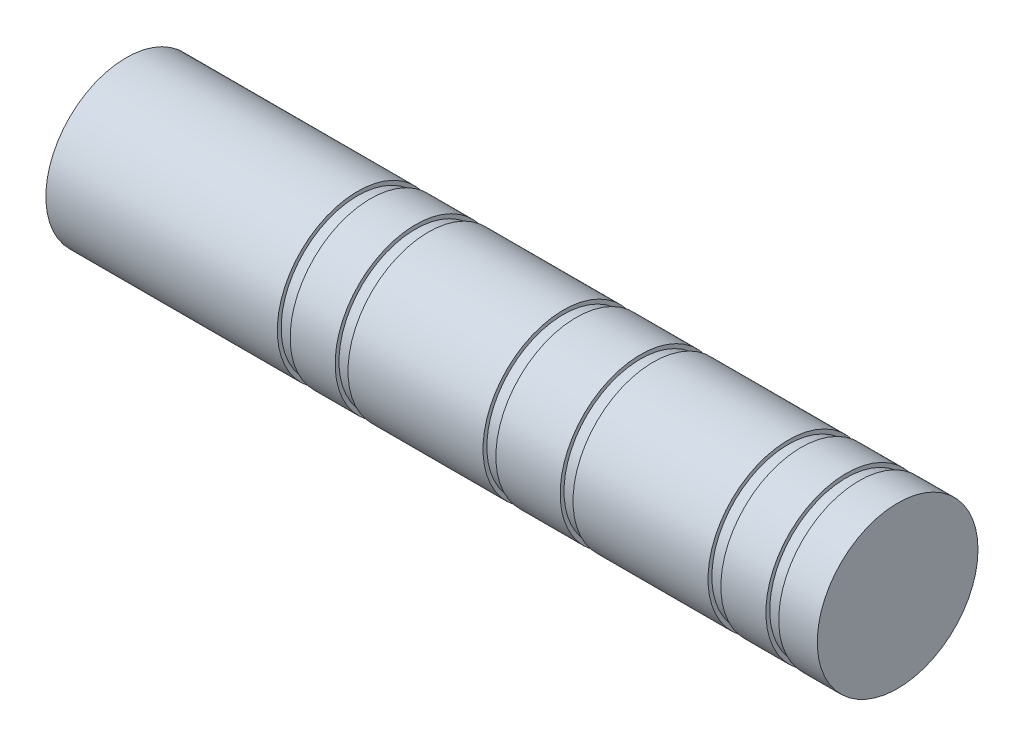
SolidWorks part; units mm, degrees
material "PE High Density"
ref_plane "Front Plane" through (0, 0, 0) normal (0, 0, 1) x (1, 0, 0)
ref_plane "Top Plane" through (0, 0, 0) normal (0, 1, 0) x (1, 0, 0)
ref_plane "Right Plane" through (0, 0, 0) normal (1, 0, 0) x (0, 0, -1)
sketch "Sketch1" plane through (0, 0, 0) normal (1, 0, 0) x (0, 0, -1)
  circle A0 centre (0, 0) radius 2.5
  dimension "D1" = 5
extrude "Boss-Extrude1" add sketch "Sketch1" along normal mid plane 24
hole_wizard "#3 Clearance Hole1" positions "Sketch2" profile "Sketch3" hole size "#3" standard "ANSI Inch"
sketch "Sketch2" plane through (-12, 0, 0) normal (-1, 0, 0) x (0, 0, 1)
  point P0 (0, 0)
sketch "Sketch3" plane through (-12, 0, 0) normal (0, 1, 0) x (0, 0, 1)
  line L0 (0, 0) -> (0, 5.8394)
  line L1 (0, 5.8394) -> (1.397, 5)
  line L2 (1.397, 5) -> (1.397, 0)
  line L5 (1.397, 0) -> (0, 0)
  line L10 (0, 5.8394) -> (-1.397, 5) construction
  line L11 (0, -6.35) -> (0, 107.95) construction
  dimension "Hole Dia." = 2.794
  dimension "Hole Depth" = 5
  dimension "Drill Angle" = 118
sketch "Sketch4" plane through (0, 0, 0) normal (0, 1, 0) x (1, 0, 0)
  line L0 (12, 2.5) -> (-12, 2.5) construction
  line L1 (10.8, 2.5) -> (10.4, 2.5)
  line L2 (10.8, 2.5) -> (10.8, 2.38)
  line L3 (10.8, 2.38) -> (10.4, 2.38)
  line L4 (10.4, 2.5) -> (10.4, 2.38)
  line L5 (12, 2.5) -> (-12, 2.5) construction
  line L6 (9, 2.5) -> (8.6, 2.5)
  line L7 (9, 2.5) -> (9, 2.38)
  line L8 (9, 2.38) -> (8.6, 2.38)
  line L9 (8.6, 2.5) -> (8.6, 2.38)
  line L10 (-2.6, 2.5) -> (-3, 2.5)
  line L11 (-2.6, 2.5) -> (-2.6, 2.38)
  line L12 (-2.6, 2.38) -> (-3, 2.38)
  line L13 (-3, 2.5) -> (-3, 2.38)
  line L14 (-4.4, 2.5) -> (-4.8, 2.5)
  line L15 (-4.4, 2.5) -> (-4.4, 2.38)
  line L16 (-4.4, 2.38) -> (-4.8, 2.38)
  line L17 (-4.8, 2.5) -> (-4.8, 2.38)
  line L18 (2, 2.5) -> (1.6, 2.5)
  line L19 (2, 2.5) -> (2, 2.38)
  line L20 (2, 2.38) -> (1.6, 2.38)
  line L21 (1.6, 2.5) -> (1.6, 2.38)
  line L22 (3, 2.5) -> (3, 4.2959) construction
  line L23 (4.4, 2.5) -> (4, 2.5)
  line L24 (4.4, 2.5) -> (4.4, 2.38)
  line L25 (4.4, 2.38) -> (4, 2.38)
  line L26 (4, 2.5) -> (4, 2.38)
  line L27 (2, 2.5) -> (3, 2.5) construction
  line L28 (3, 2.5) -> (4, 2.5) construction
  dimension "D1" = 0.12
  dimension "D2" = 1.4
  dimension "D3" = 0.4
  dimension "D4" = 1.2
  dimension "D5" = 1.4
  dimension "D6" = 12
  dimension "D7" = 7.2
  dimension "D8" = 6
  dimension "D9" = 2
ref_axis "Axis1" through (13.2, 0, 0) along (-1, 0, 0)
revolve "Cut-Revolve1" cut sketch "Sketch4" angle 360 about axis through (13.2, 0, 0) along (-1, 0, 0)
sketch "Sketch5" [suppressed] plane through (0, 0, 0) normal (0, 1, 0) x (1, 0, 0)
  line L0 (12, 2.5) -> (-12, 2.5) construction
  line L1 (9.4, 2.5) -> (9, 2.5)
  line L2 (9.4, 2.5) -> (9.4, 2.38)
  line L3 (9.4, 2.38) -> (9, 2.38)
  line L4 (9, 2.5) -> (9, 2.38)
  line L6 (-3.4, 2.5) -> (-3, 2.5)
  line L7 (-3.4, 2.5) -> (-3.4, 2.38)
  line L8 (-3.4, 2.38) -> (-3, 2.38)
  line L9 (-3, 2.5) -> (-3, 2.38)
  dimension "D1" = 12
  dimension "D2" = 0.12
  dimension "D3" = 0.4
  dimension "D4" = 2.6
  dimension "D5" = 8.6
revolve "Cut-Revolve2" [suppressed] cut sketch "Sketch5" angle 360 about axis through (13.2, 0, 0) along (-1, 0, 0)
